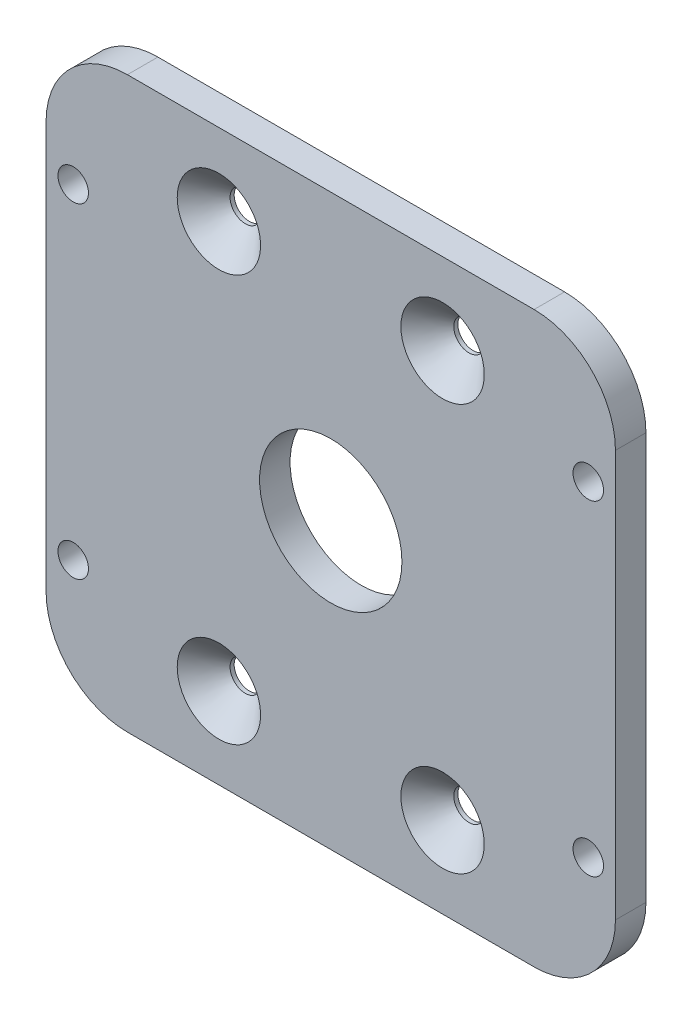
SolidWorks part; units mm, degrees
ref_plane "Спереди" through (0, 0, 0) normal (0, 0, 1) x (1, 0, 0)
ref_plane "Сверху" through (0, 0, 0) normal (0, 1, 0) x (1, 0, 0)
ref_plane "Справа" through (0, 0, 0) normal (1, 0, 0) x (0, 0, -1)
sketch "Эскиз1" plane through (0, 0, 0) normal (0, 0, 1) x (1, 0, 0)
  line L1 (8, 0) -> (48, 0)
  line L2 (0, 8) -> (0, 48)
  line L3 (8, 56) -> (48, 56)
  line L4 (56, 8) -> (56, 48)
  arc A0 (48, 56) -> (56, 48) centre (48, 48) cw
  arc A1 (48, 0) -> (56, 8) centre (48, 8) ccw
  arc A2 (8, 0) -> (0, 8) centre (8, 8) cw
  arc A3 (0, 48) -> (8, 56) centre (8, 48) cw
  point P7 (56, 56)
  point P10 (56, 0)
  point P13 (0, 0)
  point P16 (0, 56)
  dimension "D3" = 8
  dimension "D1" = 56
  dimension "D2" = 56
extrude "Бобышка-Вытянуть1" add sketch "Эскиз1" along normal blind 3
sketch "Эскиз2" plane through (0, 0, 3) normal (0, 0, 1) x (1, 0, 0)
  line L0 (8, 0) -> (48, 0) construction
  line L1 (0, 48) -> (0, 8) construction
  circle A0 centre (28, 28) radius 7
  point P4 (28, 0)
  point P7 (0, 28)
  dimension "D1" = 14
  dimension "D2" = 0
  dimension "D3" = 0
extrude "Вырез-Вытянуть1" cut sketch "Эскиз2" against normal through all
sketch "Эскиз3" plane through (0, 0, 3) normal (0, 0, 1) x (1, 0, 0)
  circle A0 centre (2.67, 12) radius 1.5
  circle A1 centre (28, 28) radius 7 construction
  circle A2 centre (53.33, 12) radius 1.5
  circle A3 centre (53.33, 44) radius 1.5
  circle A4 centre (2.67, 44) radius 1.5
  dimension "D1" = 3
  dimension "D3" = 16
  dimension "D2" = 25.33
  dimension "D4" = 2
  dimension "D5" = 2
extrude "Вырез-Вытянуть2" cut sketch "Эскиз3" against normal through all
sketch "Эскиз4" plane through (0, 0, 3) normal (0, 0, 1) x (1, 0, 0)
  circle A0 centre (17, 8) radius 1.5
  circle A1 centre (28, 28) radius 7 construction
  circle A2 centre (39, 8) radius 1.5
  circle A3 centre (39, 48) radius 1.5
  circle A4 centre (17, 48) radius 1.5
  dimension "D1" = 3
  dimension "D3" = 20
  dimension "D2" = 11
  dimension "D4" = 2
  dimension "D5" = 2
extrude "Вырез-Вытянуть3" cut sketch "Эскиз4" against normal through all
chamfer "Фаска1" distance 2.6 angle 45 4 edges at (40.5, 8, 3) (18.5, 8, 3) (40.5, 48, 3) (18.5, 48, 3)
